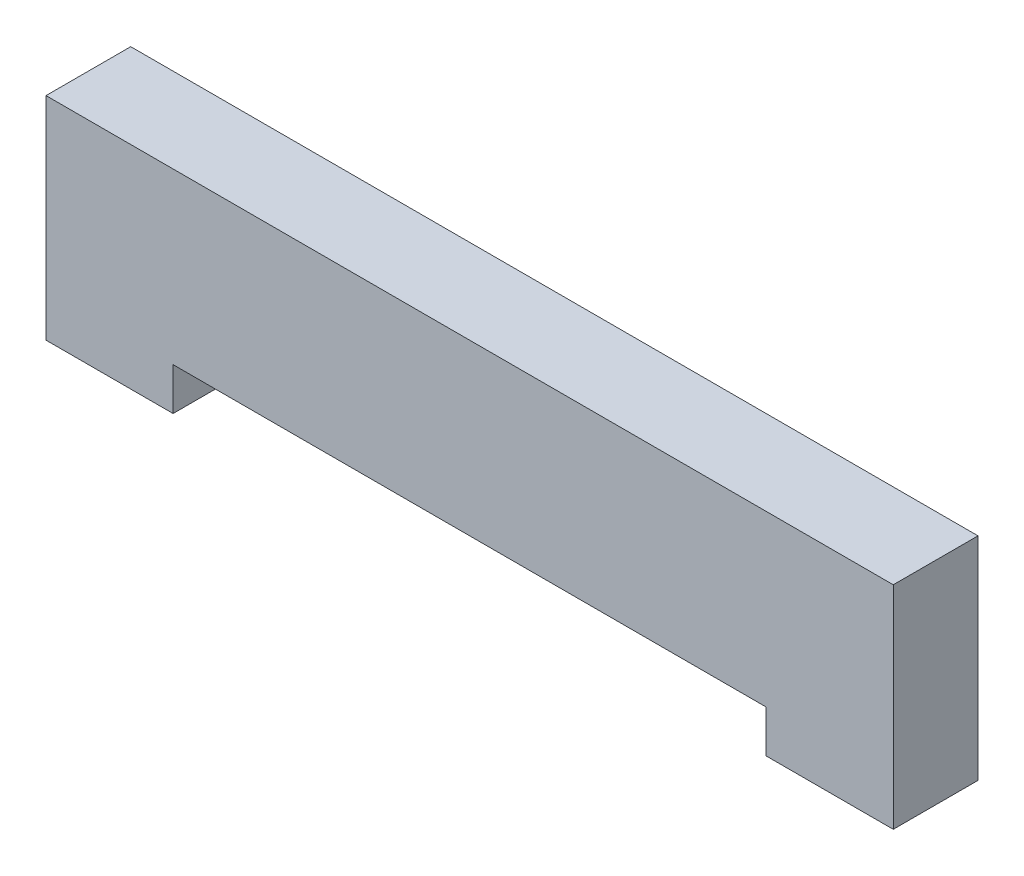
SolidWorks part; units mm, degrees
ref_plane "Plan de face" through (0, 0, 0) normal (0, 0, 1) x (1, 0, 0)
ref_plane "Plan de dessus" through (0, 0, 0) normal (0, 1, 0) x (1, 0, 0)
ref_plane "Plan de droite" through (0, 0, 0) normal (1, 0, 0) x (0, 0, -1)
sketch "Esquisse1" plane through (0, 0, 0) normal (0, 1, 0) x (1, 0, 0)
  line L0 (0, 0) -> (50, 0) construction
  line L1 (0, 0) -> (-50, 0) construction
  line L2 (50, 0) -> (50, 5)
  line L3 (50, 0) -> (50, -5)
  line L4 (50, -5) -> (-50, -5)
  line L5 (-50, -5) -> (-50, 5)
  line L6 (-50, 5) -> (50, 5)
  dimension "D1" = 5
  dimension "D2" = 5
extrude "Boss.-Extru.1" add sketch "Esquisse1" along normal blind 25
sketch "Esquisse2" plane through (0, 0, 5) normal (0, 0, 1) x (1, 0, 0)
  line L0 (0, 0) -> (35, 0)
  line L1 (-50, 0) -> (50, 0) construction
  line L2 (35, 0) -> (35, 5)
  line L3 (35, 5) -> (-35, 5)
  line L4 (-35, 5) -> (-35, 0)
  line L5 (-35, 0) -> (0, 0)
extrude "Enlèv. mat.-Extru.1" cut sketch "Esquisse2" against normal up to next
sketch "Esquisse3" plane through (0, 0, 0) normal (0, -1, 0) x (1, 0, 0)
  line L0 (35, -5) -> (50, 5) construction
  line L1 (35, 5) -> (50, -5) construction
  line L2 (-50, -5) -> (-35, 5) construction
  line L3 (-35, 5) -> (-35, -5) construction
  line L4 (-35, -5) -> (-50, 5) construction
  line L5 (-50, -5) -> (-50, 5) construction
  line L6 (-50, 5) -> (-35, 5) construction
  line L7 (-42.5, 0) -> (42.5, 0) construction
  circle A0 centre (-42.5, 0) radius 2
  circle A1 centre (42.5, 0) radius 2
  dimension "D1" = 85
extrude "Enlèv. mat.-Extru.2" cut sketch "Esquisse3" against normal blind 15
